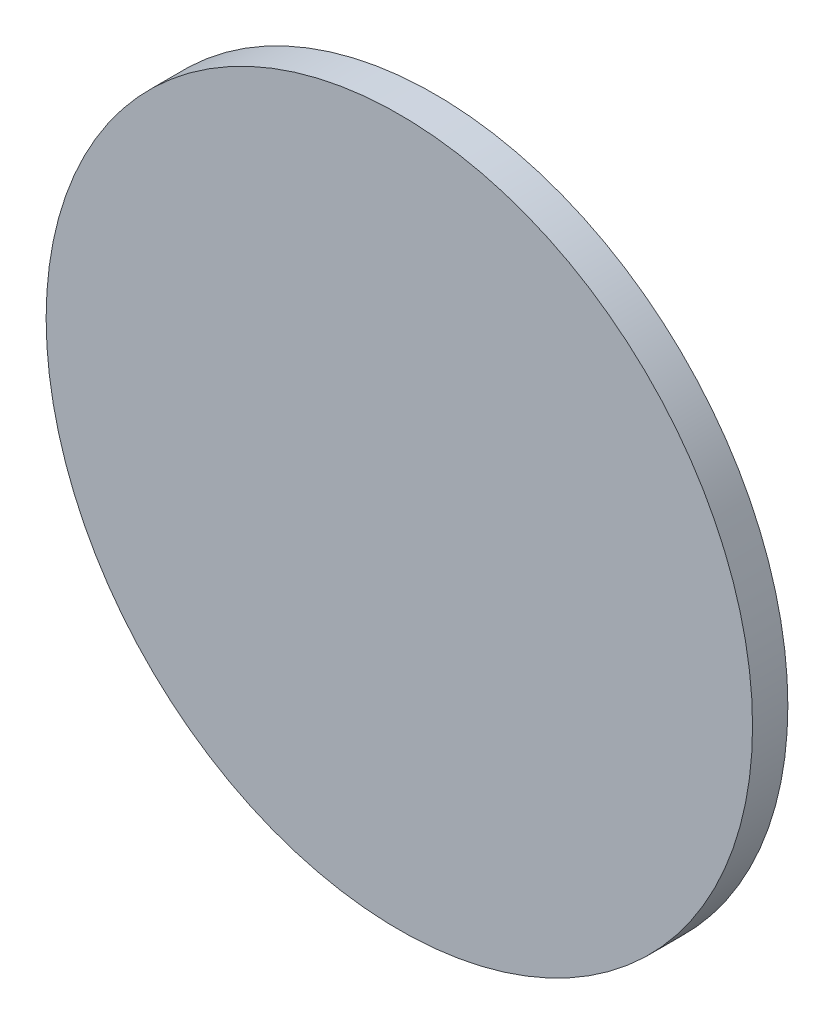
SolidWorks part; units mm, degrees
ref_plane "Front Plane" through (0, 0, 0) normal (0, 0, 1) x (1, 0, 0)
ref_plane "Top Plane" through (0, 0, 0) normal (0, 1, 0) x (1, 0, 0)
ref_plane "Right Plane" through (0, 0, 0) normal (1, 0, 0) x (0, 0, -1)
sketch "Sketch1" plane through (0, 0, 0) normal (0, 0, 1) x (1, 0, 0)
  circle A0 centre (0, 0) radius 30
  dimension "D1" = 60
extrude "Boss-Extrude1" add sketch "Sketch1" along normal blind 3
